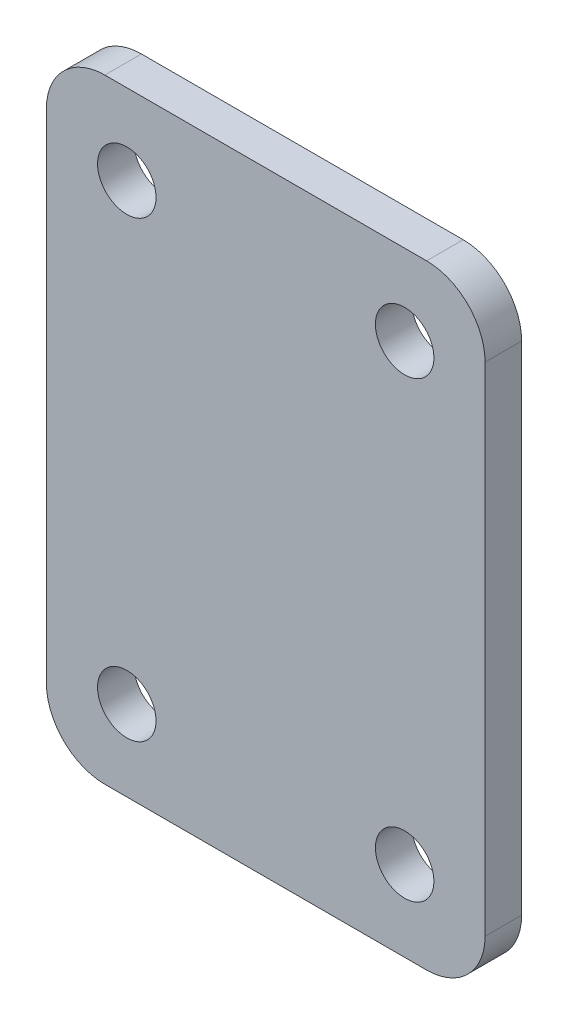
SolidWorks part; units mm, degrees
ref_plane "Front Plane" through (0, 0, 0) normal (0, 0, 1) x (1, 0, 0)
ref_plane "Top Plane" through (0, 0, 0) normal (0, 1, 0) x (1, 0, 0)
ref_plane "Right Plane" through (0, 0, 0) normal (1, 0, 0) x (0, 0, -1)
sketch "Sketch1" plane through (0, 0, 0) normal (0, 0, 1) x (1, 0, 0)
  line L0 (0, 0) -> (60, 0) construction
  line L3 (-15.5, 21) -> (-15.5, 15.5) construction
  line L8 (-21, 21) -> (21, 21)
  line L9 (-21, 21) -> (-21, -21)
  line L10 (-21, -21) -> (21, -21)
  line L11 (21, 21) -> (21, -21)
  line L12 (-21, 21) -> (21, -21) construction
  line L13 (-21, -21) -> (21, 21) construction
  line L14 (-15.5, 15.5) -> (-21, 15.5) construction
  line L15 (34, 15.5) -> (34, -15.5) construction
  line L16 (21, 21) -> (47, 21)
  line L17 (21, 21) -> (21, -149.1981)
  line L18 (21, -149.1981) -> (47, -149.1981)
  line L19 (47, 21) -> (47, -149.1981)
  circle A0 centre (0, 0) radius 17 construction
  circle A1 centre (60, 0) radius 47 construction
  circle A2 centre (0, 0) radius 15
  circle A3 centre (60, 0) radius 45
  circle A6 centre (-15.5, 15.5) radius 2
  circle A7 centre (15.5, 15.5) radius 2
  circle A8 centre (-15.5, -15.5) radius 2
  circle A9 centre (15.5, -15.5) radius 2
  circle A10 centre (34, 15.5) radius 2
  circle A11 centre (34, -15.5) radius 2
  circle A12 centre (0, 0) radius 8.5
  circle A14 centre (60, 0) radius 8.5
  point P33 (34, 21)
  dimension "D1" = 34
  dimension "D2" = 94
  dimension "D3" = 30
  dimension "D4" = 90
  dimension "D5" = 17
  dimension "D9" = 4
  dimension "D13" = 4
  dimension "D7" = 42
  dimension "D8" = 31
  dimension "D10" = 26
sketch "Sketch2" plane through (0, 0, 0) normal (0, 0, 1) x (1, 0, 0)
  line L0 (-21, -21) -> (21, -21) construction
  line L1 (-21, 21) -> (117, 21)
  line L2 (-21, 21) -> (-21, -21)
  line L3 (-21, -21) -> (117, -21)
  line L4 (117, 21) -> (117, -21)
  circle A1 centre (15.5, -15.5) radius 2 construction
  circle A3 centre (15.5, 15.5) radius 2 construction
  circle A12 centre (111.5, 15.5) radius 2
  circle A13 centre (111.5, -15.5) radius 2
  circle A14 centre (60, 0) radius 47 construction
  circle A15 centre (111.5, -15.5) radius 3.175 construction
  circle A17 centre (34, -15.5) radius 2 construction
  circle A18 centre (34, 15.5) radius 2 construction
  circle A19 centre (34, -15.5) radius 2
  circle A20 centre (34, 15.5) radius 2
  circle A22 centre (0, 0) radius 3.5
  circle A23 centre (60, 0) radius 8.5 construction
  circle A24 centre (60, 0) radius 8.5
  dimension "D1" = 10
  dimension "D2" = 5.5
  dimension "D3" = 6.35
  dimension "D4" = 7
extrude "Boss-Extrude1" add sketch "Sketch2" along normal mid plane 4.7625
sketch "Sketch3" plane through (0, 0, -2.3813) normal (0, 0, -1) x (-1, 0, 0)
  circle A0 centre (-34, 15.5) radius 2
  circle A1 centre (-34, -15.5) radius 4
  circle A2 centre (-34, 15.5) radius 4
  circle A3 centre (-15.5, 15.5) radius 4
  circle A4 centre (15.5, 15.5) radius 4
  circle A5 centre (-15.5, -15.5) radius 4
  circle A6 centre (15.5, -15.5) radius 4
  dimension "D1" = 4
  dimension "D2" = 8
extrude "Cut-Extrude1" cut sketch "Sketch3" against normal blind 4
sketch "Sketch4" plane through (0, 0, -2.3813) normal (0, 0, -1) x (-1, 0, 0)
  circle A0 centre (-111.5, -15.5) radius 3.175 construction
  circle A1 centre (-111.5, -15.5) radius 3.175
  circle A2 centre (-111.5, 15.5) radius 3.175
  circle A5 centre (-111.5, 15.5) radius 2
  circle A6 centre (-111.5, -15.5) radius 2
ref_plane "Plane1" through (0, 0, -11.3312) normal (0, 0, -1) x (-1, 0, 0)
extrude "Boss-Extrude2" add sketch "Sketch4" along normal blind 17.9
sketch "Sketch5" plane through (0, 0, -2.3813) normal (0, 0, -1) x (-1, 0, 0)
  line L0 (21, 21) -> (21, -21) construction
  line L1 (21, -21) -> (27.2081, -0.9386)
  line L2 (21, 21) -> (27.2081, 0.9386)
  line L3 (21, 21) -> (21, -21)
  arc A0 (27.2081, -0.9386) -> (27.2081, 0.9386) centre (24.175, 0) ccw
  point P5 (24.175, 0.7154)
  point P7 (21, 0)
  dimension "D1" = 6.35
sketch "Sketch6" plane through (0, 0, -2.3813) normal (0, 0, -1) x (-1, 0, 0)
  circle A0 centre (-15.5, 15.5) radius 2 construction
  circle A1 centre (15.5, 15.5) radius 2 construction
  circle A2 centre (15.5, -15.5) radius 2 construction
  circle A3 centre (-15.5, -15.5) radius 2 construction
  circle A16 centre (-15.5, 15.5) radius 2
  circle A17 centre (15.5, 15.5) radius 2
  circle A18 centre (15.5, -15.5) radius 2
  circle A19 centre (-15.5, -15.5) radius 2
extrude "Cut-Extrude2" cut sketch "Sketch6" against normal blind 10
extrude "Boss-Extrude3" add sketch "Sketch5" against normal up to surface (4.7625 mm away) up to face at (17.5, -15.5, 2.3812)
mirror "Mirror2" about plane through (0, 0, -11.3312) normal (0, 0, -1) of "Boss-Extrude3", "Boss-Extrude1"
sketch "Sketch7" plane through (0, 0, -20.2812) normal (0, 0, 1) x (1, 0, 0)
  circle A5 centre (-24.175, 0) radius 3.175
  arc A6 (-27.2081, 0.9386) -> (-27.2081, -0.9386) centre (-24.175, 0) ccw construction
  dimension "D1" = 6.35
extrude "Boss-Extrude4" add sketch "Sketch7" along normal up to surface (17.9 mm away) contours A5 up to face at (109.5, -15.5, -2.3813)
fillet "Fillet1" radius 6.35 8 edges at (-21, 21, -22.6625) (-21, -21, -22.6625) (117, -21, -22.6625) (117, 21, -22.6625) (117, -21, 0) (-21, -21, 0) (-21, 21, 0) (117, 21, 0)
sketch "Sketch8" plane through (0, 0, -25.0437) normal (0, 0, -1) x (-1, 0, 0)
  line L0 (16.3179, -21) -> (-110.65, -21) construction
  line L1 (-3.175, -21) -> (3.175, -21)
  line L2 (0, 0) -> (27.35, 0) construction
  arc A0 (-3.175, -21) -> (3.175, -21) centre (0, -21) ccw
  arc A1 (27.2081, -0.9386) -> (27.2081, 0.9386) centre (24.175, 0) ccw construction
  arc A2 (-3.175, 21) -> (3.175, 21) centre (0, 21) cw
  line M9 (16.3179, 21) -> (-110.65, 21)
  line M13 (-110.65, -21) -> (16.3179, -21)
  dimension "D1" = 6.35
extrude "Boss-Extrude5" add sketch "Sketch8" against normal up to surface (27.425 mm away) contours A2 M9 | A0 M13
sketch "Sketch9" plane through (0, 0, -20.2812) normal (0, 0, 1) x (1, 0, 0)
  circle A0 centre (34, -15.5) radius 4 construction
  circle A1 centre (34, 15.5) radius 4 construction
  circle A2 centre (34, -15.5) radius 4
  circle A3 centre (34, 15.5) radius 4
extrude "Cut-Extrude4" cut sketch "Sketch9" against normal blind 4
sketch "Sketch10" plane through (0, 0, 2.3813) normal (0, 0, 1) x (1, 0, 0)
  circle A0 centre (0, 0) radius 11.0046
  dimension "D1" = 22.0091
extrude "Cut-Extrude5" cut sketch "Sketch10" against normal blind 2.5
sketch "Sketch11" plane through (0, 0, 2.3813) normal (0, 0, 1) x (1, 0, 0)
  line L0 (3.175, 21) -> (110.65, 21) construction
  line L1 (45, 21) -> (75, 21) construction
  line L2 (45, 21) -> (45, -21) construction
  line L3 (45, -21) -> (75, -21) construction
  line L4 (75, 21) -> (75, -21) construction
  line L5 (3.175, -21) -> (110.65, -21) construction
  line L6 (60, 0) -> (60, 21) construction
  line L7 (45, 15.5) -> (50.5, 15.5) construction
  line L8 (50.5, 15.5) -> (50.5, 21) construction
  line L9 (60, 0) -> (75, 0) construction
  circle A0 centre (50.5, 15.5) radius 1.65
  circle A2 centre (34, 15.5) radius 2 construction
  circle A3 centre (34, 15.5) radius 2 construction
  circle A4 centre (69.5, 15.5) radius 1.65
  circle A5 centre (69.5, -15.5) radius 1.65
  circle A6 centre (50.5, -15.5) radius 1.65
  point P23 (0, 0)
  dimension "D2" = 3.3
  dimension "D1" = 30
extrude "Cut-Extrude6" cut sketch "Sketch11" against normal through all both and the other way through all
sketch "Sketch12" plane through (0, 0, 2.3813) normal (0, 0, 1) x (1, 0, 0)
  line L0 (60, 0) -> (60, 21) construction
  line L1 (49, 21) -> (71, 21)
  line L2 (45, 17) -> (45, -17)
  line L3 (49, -21) -> (71, -21)
  line L4 (75, 17) -> (75, -17)
  line L5 (60, 0) -> (60, 21) construction
  line L6 (60, 0) -> (75, 0) construction
  line L7 (60, 0) -> (75, 0) construction
  circle A1 centre (50.5, 15.5) radius 2
  circle A2 centre (69.5, 15.5) radius 2
  circle A4 centre (69.5, -15.5) radius 2
  circle A5 centre (50.5, -15.5) radius 2
  arc A6 (75, -17) -> (71, -21) centre (71, -17) cw
  arc A7 (49, -21) -> (45, -17) centre (49, -17) cw
  arc A8 (75, 17) -> (71, 21) centre (71, 17) ccw
  arc A9 (49, 21) -> (45, 17) centre (49, 17) ccw
  point P20 (75, -21)
  point P27 (45, 21)
  dimension "D1" = 4
  dimension "D2" = 4
extrude "Boss-Extrude6" add sketch "Sketch12" along normal blind 2.5 separate body
delete or keep bodies "Body-Delete/Keep 1" type keep bodies bodies 117
